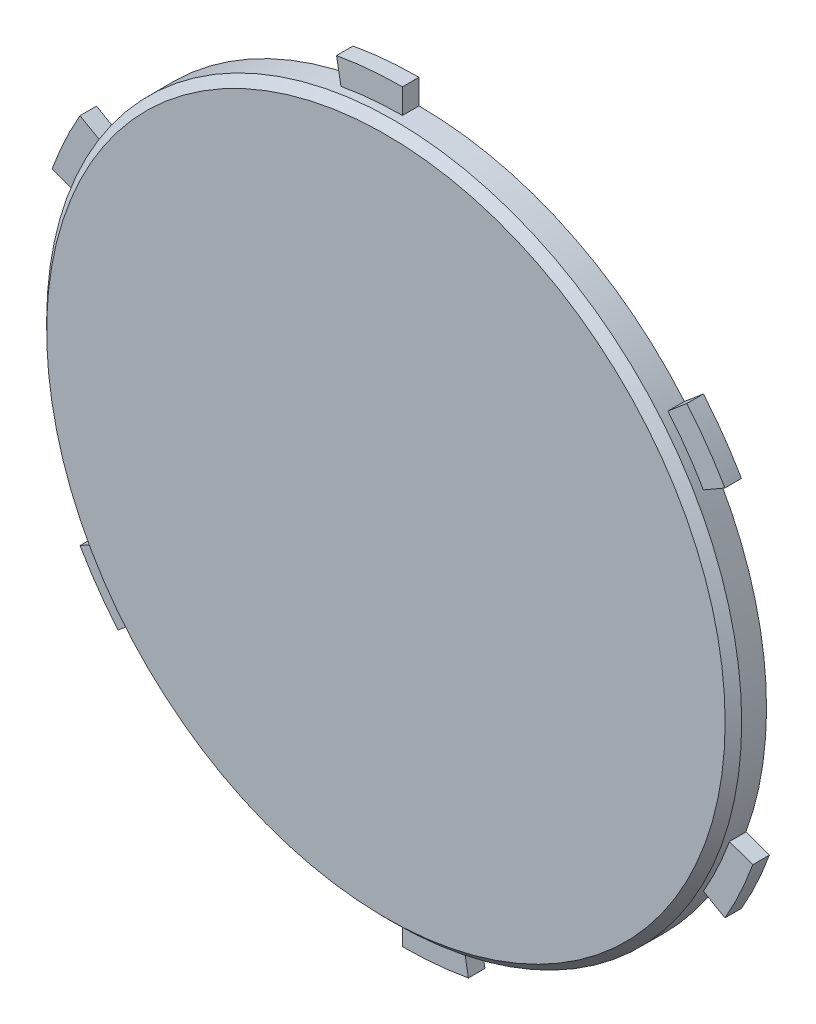
SolidWorks part; units mm, degrees
ref_plane "前视基准面" through (0, 0, 0) normal (0, 0, 1) x (1, 0, 0)
ref_plane "上视基准面" through (0, 0, 0) normal (0, 1, 0) x (1, 0, 0)
ref_plane "右视基准面" through (0, 0, 0) normal (1, 0, 0) x (0, 0, -1)
sketch "草图1" plane through (0, 0, 0) normal (0, 0, 1) x (1, 0, 0)
  circle A0 centre (0, 0) radius 21
  dimension "D1" = 42
extrude "凸台-拉伸1" add sketch "草图1" along normal blind 2
sketch "草图2" plane through (0, 0, 2) normal (0, 0, 1) x (1, 0, 0)
  circle A0 centre (0, 0) radius 21
  dimension "D1" = 42
extrude "凸台-拉伸2" [suppressed] add sketch "草图2" along normal blind 1
sketch "草图3" plane through (0, 0, 0) normal (0, 0, -1) x (-1, 0, 0)
  line L0 (0, 22.5) -> (0, 21)
  line L13 (3.9842, 22.1444) -> (3.7186, 20.6681)
  line L14 (19.4856, 11.25) -> (18.1865, 10.5)
  line L15 (21.1697, 7.6218) -> (19.7584, 7.1137)
  line L16 (19.4856, -11.25) -> (18.1865, -10.5)
  line L17 (17.1856, -14.5226) -> (16.0399, -13.5544)
  line L18 (0, -22.5) -> (0, -21)
  line L19 (-3.9842, -22.1444) -> (-3.7186, -20.6681)
  line L20 (-19.4856, -11.25) -> (-18.1865, -10.5)
  line L21 (-21.1697, -7.6218) -> (-19.7584, -7.1137)
  line L22 (-19.4856, 11.25) -> (-18.1865, 10.5)
  line L23 (-17.1856, 14.5226) -> (-16.0399, 13.5544)
  arc A12 (3.7186, 20.6681) -> (0, 21) centre (0, 0) ccw
  arc A13 (3.9842, 22.1444) -> (0, 22.5) centre (0, 0) ccw
  arc A14 (21.1697, 7.6218) -> (19.4856, 11.25) centre (0, 0) ccw
  arc A15 (19.7584, 7.1137) -> (18.1865, 10.5) centre (0, 0) ccw
  arc A16 (17.1856, -14.5226) -> (19.4856, -11.25) centre (0, 0) ccw
  arc A17 (16.0399, -13.5544) -> (18.1865, -10.5) centre (0, 0) ccw
  arc A18 (-3.9842, -22.1444) -> (0, -22.5) centre (0, 0) ccw
  arc A19 (-3.7186, -20.6681) -> (0, -21) centre (0, 0) ccw
  arc A20 (-21.1697, -7.6218) -> (-19.4856, -11.25) centre (0, 0) ccw
  arc A21 (-19.7584, -7.1137) -> (-18.1865, -10.5) centre (0, 0) ccw
  arc A22 (-17.1856, 14.5226) -> (-19.4856, 11.25) centre (0, 0) ccw
  arc A23 (-16.0399, 13.5544) -> (-18.1865, 10.5) centre (0, 0) ccw
  point P27 (0, 0)
  dimension "D1" = 45
  dimension "D2" = 4
extrude "凸台-拉伸3" add sketch "草图3" against normal blind 1
chamfer "倒角1" distance 0.5 angle 45 1 edges at (21, 0, 2)
